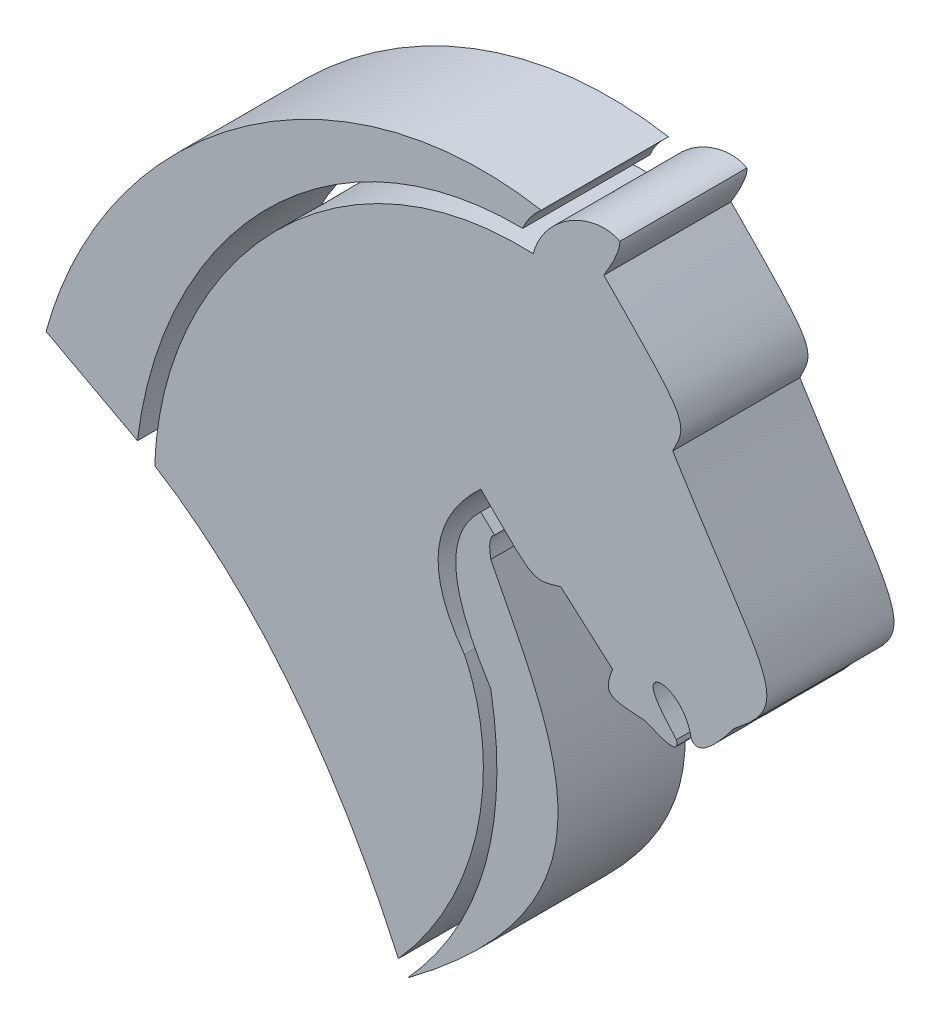
SolidWorks part; units mm, degrees
ref_plane "Front Plane" through (0, 0, 0) normal (0, 0, 1) x (1, 0, 0)
ref_plane "Top Plane" through (0, 0, 0) normal (0, 1, 0) x (1, 0, 0)
ref_plane "Right Plane" through (0, 0, 0) normal (1, 0, 0) x (0, 0, -1)
sketch "Sketch60" plane through (0, 0, 0) normal (0, 0, 1) x (1, 0, 0)
  spline S0 degree 3 poles (7.8995, 25.0432) (-7.6161, 25.2572) (-20.5493, 10.9756) (-22.404, -4.5755) knots 0 0 0 0 1 1 1 1
  spline S1 degree 3 poles (-29.5947, -0.7234) (-25.1005, 15.7552) (-7.6585, 30.0081) (9.3548, 27.012) knots 0 0 0 0 1 1 1 1
  spline S2 degree 3 poles (-21.0344, -5.6028) (-20.6586, 8.5535) (-7.291, 24.4778) (8.7173, 23.7281) knots 0 0 0 0 1 1 1 1
  spline S3 degree 3 poles (8.7173, 23.7281) (9.6631, 27.1728) (13.7157, 29.0121) (15.531, 27.9716) knots 0 0 0 0 1 1 1 1
  spline S4 degree 2 poles (15.531, 27.9716) (15.6027, 27.2121) (14.2824, 25.0432) knots 0 0 0 1 1 1
  spline S5 degree 3 poles (14.2824, 25.0432) (20.7856, 18.3949) (21.0008, 18.2445) (19.7003, 15.7779) knots 0 0 0 0 1 1 1 1
  spline S6 degree 3 poles (24.5166, -0.7234) (29.3878, 3.0666) (27.1417, 3.6792) (19.7003, 15.7779) knots 0 0 0 0 1 1 1 1
  spline S7 degree 2 poles (24.5166, -0.7234) (21.7534, -4.3974) (21.1262, -3.0177) knots 0 0 0 1 1 1
  spline S8 degree 3 poles (21.1262, -3.0177) (20.8963, -1.3897) (19.3083, -0.1798) (18.4084, -0.6102) knots 0 0 0 0 1 1 1 1
  spline S9 degree 3 poles (18.4084, -0.6102) (17.5867, -1.0798) (18.9328, -2.5669) (19.9894, -3.7408) knots 0 0 0 0 1 1 1 1
  spline S10 degree 2 poles (19.9894, -3.7408) (20.3806, -4.9928) (17.5319, -3.6782) knots 0 0 0 1 1 1
  spline S11 degree 3 poles (17.5319, -3.6782) (14.6251, -3.5373) (14.1973, -3.4091) (14.9643, -1.4533) knots 0 0 0 0 1 1 1 1
  spline S12 degree 1 poles (14.9643, -1.4533) (10.8961, 2.1266) knots 0 0 1 1
  spline S13 degree 3 poles (10.8961, 2.1266) (8.5588, 1.4131) (8.8013, 1.4774) (4.5977, 5.6288) knots 0 0 0 0 1 1 1 1
  spline S14 degree 2 poles (4.5977, 5.6288) (-1.3896, 0.0431) (3.3103, -6.2691) knots 0 0 0 1 1 1
  spline S15 degree 3 poles (3.3103, -6.2691) (6.1906, -12.1629) (5.143, -21.7014) (-1.8713, -29.5871) knots 0 0 0 0 1 1 1 1
  spline S16 degree 2 poles (-21.0344, -5.6028) (-9.5989, -12.6722) (-1.8713, -29.5871) knots 0 0 0 1 1 1
  spline S17 degree 1 poles (-29.5947, -0.7234) (-22.404, -4.5755) knots 0 0 1 1
  spline S18 degree 2 poles (9.3548, 27.012) (8.3375, 26.1176) (7.8995, 25.0432) knots 0 0 0 1 1 1
  spline S19 degree 3 poles (4.5977, 4.0778) (1.5754, 1.1985) (2.211, -2.6307) (5.3845, -7.5625) knots 0 0 0 0 1 1 1 1
  spline S20 degree 2 poles (5.3845, -7.5625) (7.711, -20.7718) (-1.1688, -30.5559) knots 0 0 0 1 1 1
  spline S21 degree 3 poles (-1.1688, -30.5559) (16.2809, -17.4811) (10.776, -9.3165) (5.3845, 1.2346) knots 0 0 0 0 1 1 1 1
  spline S22 degree 2 poles (5.3845, 1.2346) (5.1244, 2.7099) (5.6879, 3.0438) knots 0 0 0 1 1 1
  spline S23 degree 1 poles (4.5977, 4.0778) (5.6879, 3.0438) knots 0 0 1 1
extrude "Boss-Extrude6" add sketch "Sketch60" along normal blind 10 from offset 75 offset against normal yes
